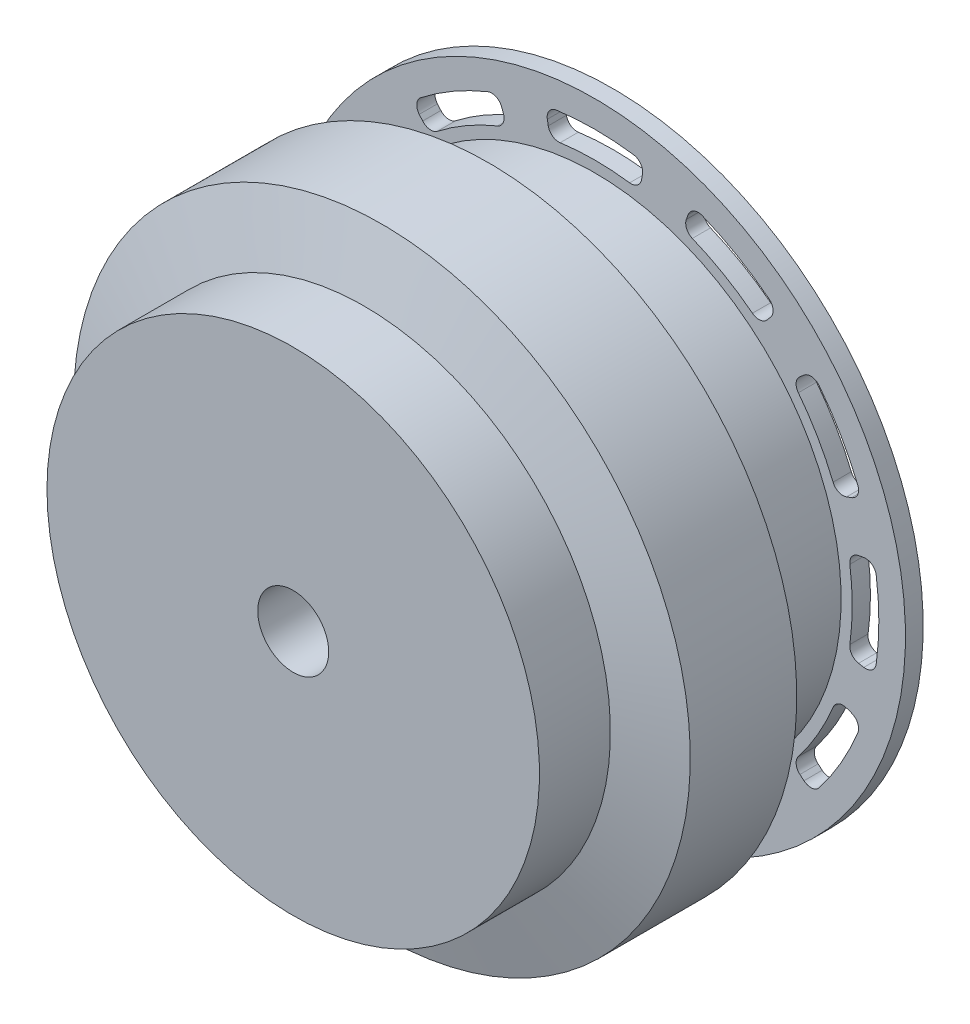
SolidWorks part; units mm, degrees
ref_plane "Plan de face" through (0, 0, 0) normal (0, 0, 1) x (1, 0, 0)
ref_plane "Plan de dessus" through (0, 0, 0) normal (0, 1, 0) x (1, 0, 0)
ref_plane "Plan de droite" through (0, 0, 0) normal (1, 0, 0) x (0, 0, -1)
sketch "Esquisse2" plane through (0, 0, 0) normal (0, 1, 0) x (1, 0, 0)
  line L0 (-13.875, -5) -> (-17.375, -5) construction
  line L1 (-17.375, -5) -> (-17.375, -13) construction
  line L2 (-13.875, 0) -> (-13.875, -3.6273) construction
  line L3 (-13.875, -3.6273) -> (15.125, -3.6273) construction
  line L4 (15.125, -3.6273) -> (15.125, 0) construction
  line L5 (0, 11.4518) -> (0, -9.7046) construction
  line L6 (-17.5, 1) -> (-17.5, 0) construction
  line L7 (-17.375, -13) -> (-13.875, -13) construction
  line L8 (-8.9586, -1.6125) -> (8.1668, -1.6125) construction
  line L9 (-17.5, 1) -> (-17.5, 0)
  line L10 (-17.5, 0) -> (-13.875, 0)
  line L11 (-13.875, 0) -> (-13.875, -5)
  line L12 (0, -1.6125) -> (0, -17)
  line L13 (0, -17) -> (-13.875, -17)
  line L14 (-17.375, -9) -> (-13.875, -9) construction
  line L15 (-17.375, -6) -> (-13.875, -5)
  line L16 (-17.375, -12) -> (-13.875, -13)
  line L17 (-17.375, -6) -> (-17.375, -12)
  line L18 (-13.875, -13) -> (-13.875, -17)
  spline S0 degree 3 poles (-17.5, 1) (1.0335, 1.3329) (-9.7673, -1.5554) (0, -1.6125) knots 0 0 0 0 1 1 1 1
  spline S1 degree 3 poles (17.5, 1) (-1.0335, 1.3329) (9.7673, -1.5554) (0, -1.6125) knots 0 0 0 0 1 1 1 1
  point P5 (0, 0)
  dimension "D1" = 29
  dimension "D2" = 1
  dimension "D3" = 13.875
  dimension "D4" = 17
  dimension "D5" = 5
  dimension "D6" = 8
  dimension "D7" = 3.5
  dimension "D8" = 6
revolve "Révolution1" add sketch "Esquisse2" angle 360 about L5
sketch "Esquisse3" plane through (0, 0, 0) normal (0, 0, 1) x (1, 0, 0)
  circle A0 centre (0, 0) radius 3
  circle A1 centre (0, 0) radius 2 construction
  dimension "D1" = 4
  dimension "D2" = 6
extrude "Boss.-Extru.1" add sketch "Esquisse3" along normal blind 3.4 separate body
fillet "Congé1" radius 1 1 edges at (3, 0, 0)
sketch "Esquisse4" plane through (0, 0, 0) normal (0, 0, 1) x (1, 0, 0)
  line L0 (0, 16.53) -> (0, 13.5518) construction
  line L1 (-2.6806, 15.153) -> (-2.6283, 14.8574)
  line L2 (2.6806, 15.153) -> (2.6283, 14.8574)
  line L3 (5.255, 14.4632) -> (5.1525, 14.181)
  line L4 (9.898, 11.7826) -> (9.7049, 11.5527)
  line L5 (11.7826, 9.898) -> (11.5527, 9.7049)
  line L6 (14.4632, 5.255) -> (14.181, 5.1525)
  line L7 (15.153, 2.6806) -> (14.8574, 2.6283)
  line L8 (15.153, -2.6806) -> (14.8574, -2.6283)
  line L9 (14.4632, -5.255) -> (14.181, -5.1525)
  line L10 (11.7826, -9.898) -> (11.5527, -9.7049)
  line L11 (9.898, -11.7826) -> (9.7049, -11.5527)
  line L12 (5.255, -14.4632) -> (5.1525, -14.181)
  line L13 (2.6806, -15.153) -> (2.6283, -14.8574)
  line L14 (-2.6806, -15.153) -> (-2.6283, -14.8574)
  line L15 (-5.255, -14.4632) -> (-5.1525, -14.181)
  line L16 (-9.898, -11.7826) -> (-9.7049, -11.5527)
  line L17 (-11.7826, -9.898) -> (-11.5527, -9.7049)
  line L18 (-14.4632, -5.255) -> (-14.181, -5.1525)
  line L19 (-15.153, -2.6806) -> (-14.8574, -2.6283)
  line L20 (-15.153, 2.6806) -> (-14.8574, 2.6283)
  line L21 (-14.4632, 5.255) -> (-14.181, 5.1525)
  line L22 (-11.7826, 9.898) -> (-11.5527, 9.7049)
  line L23 (-9.898, 11.7826) -> (-9.7049, 11.5527)
  line L24 (-5.255, 14.4632) -> (-5.1525, 14.181)
  arc A0 (2.1712, 15.852) -> (-2.1712, 15.852) centre (0, 0) ccw
  arc A3 (1.9565, 14.3674) -> (-1.9565, 14.3674) centre (0, 0) ccw
  arc A4 (2.6283, 14.8574) -> (1.9565, 14.3674) centre (2.0375, 14.9619) cw
  arc A5 (2.6806, 15.153) -> (2.1712, 15.852) centre (2.0898, 15.2575) ccw
  arc A6 (-2.6806, 15.153) -> (-2.1712, 15.852) centre (-2.0898, 15.2575) cw
  arc A7 (-2.6283, 14.8574) -> (-1.9565, 14.3674) centre (-2.0375, 14.9619) ccw
  arc A8 (9.8063, 12.6426) -> (6.0457, 14.8138) centre (0, 0) ccw
  arc A9 (5.255, 14.4632) -> (6.0457, 14.8138) centre (5.819, 14.2583) cw
  arc A10 (9.898, 11.7826) -> (9.8063, 12.6426) centre (9.4386, 12.1685) ccw
  arc A11 (5.1525, 14.181) -> (5.4893, 13.4208) centre (5.7164, 13.9761) ccw
  arc A12 (8.8781, 11.4643) -> (5.4893, 13.4208) centre (0, 0) ccw
  arc A13 (9.7049, 11.5527) -> (8.8781, 11.4643) centre (9.2455, 11.9387) cw
  arc A14 (14.8138, 6.0457) -> (12.6426, 9.8063) centre (0, 0) ccw
  arc A15 (11.7826, 9.898) -> (12.6426, 9.8063) centre (12.1685, 9.4386) cw
  arc A16 (14.4632, 5.255) -> (14.8138, 6.0457) centre (14.2583, 5.819) ccw
  arc A17 (11.5527, 9.7049) -> (11.4643, 8.8781) centre (11.9387, 9.2455) ccw
  arc A18 (13.4208, 5.4893) -> (11.4643, 8.8781) centre (0, 0) ccw
  arc A19 (14.181, 5.1525) -> (13.4208, 5.4893) centre (13.9761, 5.7164) cw
  arc A20 (15.852, -2.1712) -> (15.852, 2.1712) centre (0, 0) ccw
  arc A21 (15.153, 2.6806) -> (15.852, 2.1712) centre (15.2575, 2.0898) cw
  arc A22 (15.153, -2.6806) -> (15.852, -2.1712) centre (15.2575, -2.0898) ccw
  arc A23 (14.8574, 2.6283) -> (14.3674, 1.9565) centre (14.9619, 2.0375) ccw
  arc A24 (14.3674, -1.9565) -> (14.3674, 1.9565) centre (0, 0) ccw
  arc A25 (14.8574, -2.6283) -> (14.3674, -1.9565) centre (14.9619, -2.0375) cw
  arc A26 (12.6426, -9.8063) -> (14.8138, -6.0457) centre (0, 0) ccw
  arc A27 (14.4632, -5.255) -> (14.8138, -6.0457) centre (14.2583, -5.819) cw
  arc A28 (11.7826, -9.898) -> (12.6426, -9.8063) centre (12.1685, -9.4386) ccw
  arc A29 (14.181, -5.1525) -> (13.4208, -5.4893) centre (13.9761, -5.7164) ccw
  arc A30 (11.4643, -8.8781) -> (13.4208, -5.4893) centre (0, 0) ccw
  arc A31 (11.5527, -9.7049) -> (11.4643, -8.8781) centre (11.9387, -9.2455) cw
  arc A32 (6.0457, -14.8138) -> (9.8063, -12.6426) centre (0, 0) ccw
  arc A33 (9.898, -11.7826) -> (9.8063, -12.6426) centre (9.4386, -12.1685) cw
  arc A34 (5.255, -14.4632) -> (6.0457, -14.8138) centre (5.819, -14.2583) ccw
  arc A35 (9.7049, -11.5527) -> (8.8781, -11.4643) centre (9.2455, -11.9387) ccw
  arc A36 (5.4893, -13.4208) -> (8.8781, -11.4643) centre (0, 0) ccw
  arc A37 (5.1525, -14.181) -> (5.4893, -13.4208) centre (5.7164, -13.9761) cw
  arc A38 (-2.1712, -15.852) -> (2.1712, -15.852) centre (0, 0) ccw
  arc A39 (2.6806, -15.153) -> (2.1712, -15.852) centre (2.0898, -15.2575) cw
  arc A40 (-2.6806, -15.153) -> (-2.1712, -15.852) centre (-2.0898, -15.2575) ccw
  arc A41 (2.6283, -14.8574) -> (1.9565, -14.3674) centre (2.0375, -14.9619) ccw
  arc A42 (-1.9565, -14.3674) -> (1.9565, -14.3674) centre (0, 0) ccw
  arc A43 (-2.6283, -14.8574) -> (-1.9565, -14.3674) centre (-2.0375, -14.9619) cw
  arc A44 (-9.8063, -12.6426) -> (-6.0457, -14.8138) centre (0, 0) ccw
  arc A45 (-5.255, -14.4632) -> (-6.0457, -14.8138) centre (-5.819, -14.2583) cw
  arc A46 (-9.898, -11.7826) -> (-9.8063, -12.6426) centre (-9.4386, -12.1685) ccw
  arc A47 (-5.1525, -14.181) -> (-5.4893, -13.4208) centre (-5.7164, -13.9761) ccw
  arc A48 (-8.8781, -11.4643) -> (-5.4893, -13.4208) centre (0, 0) ccw
  arc A49 (-9.7049, -11.5527) -> (-8.8781, -11.4643) centre (-9.2455, -11.9387) cw
  arc A50 (-14.8138, -6.0457) -> (-12.6426, -9.8063) centre (0, 0) ccw
  arc A51 (-11.7826, -9.898) -> (-12.6426, -9.8063) centre (-12.1685, -9.4386) cw
  arc A52 (-14.4632, -5.255) -> (-14.8138, -6.0457) centre (-14.2583, -5.819) ccw
  arc A53 (-11.5527, -9.7049) -> (-11.4643, -8.8781) centre (-11.9387, -9.2455) ccw
  arc A54 (-13.4208, -5.4893) -> (-11.4643, -8.8781) centre (0, 0) ccw
  arc A55 (-14.181, -5.1525) -> (-13.4208, -5.4893) centre (-13.9761, -5.7164) cw
  arc A56 (-15.852, 2.1712) -> (-15.852, -2.1712) centre (0, 0) ccw
  arc A57 (-15.153, -2.6806) -> (-15.852, -2.1712) centre (-15.2575, -2.0898) cw
  arc A58 (-15.153, 2.6806) -> (-15.852, 2.1712) centre (-15.2575, 2.0898) ccw
  arc A59 (-14.8574, -2.6283) -> (-14.3674, -1.9565) centre (-14.9619, -2.0375) ccw
  arc A60 (-14.3674, 1.9565) -> (-14.3674, -1.9565) centre (0, 0) ccw
  arc A61 (-14.8574, 2.6283) -> (-14.3674, 1.9565) centre (-14.9619, 2.0375) cw
  arc A62 (-12.6426, 9.8063) -> (-14.8138, 6.0457) centre (0, 0) ccw
  arc A63 (-14.4632, 5.255) -> (-14.8138, 6.0457) centre (-14.2583, 5.819) cw
  arc A64 (-11.7826, 9.898) -> (-12.6426, 9.8063) centre (-12.1685, 9.4386) ccw
  arc A65 (-14.181, 5.1525) -> (-13.4208, 5.4893) centre (-13.9761, 5.7164) ccw
  arc A66 (-11.4643, 8.8781) -> (-13.4208, 5.4893) centre (0, 0) ccw
  arc A67 (-11.5527, 9.7049) -> (-11.4643, 8.8781) centre (-11.9387, 9.2455) cw
  arc A68 (-6.0457, 14.8138) -> (-9.8063, 12.6426) centre (0, 0) ccw
  arc A69 (-9.898, 11.7826) -> (-9.8063, 12.6426) centre (-9.4386, 12.1685) cw
  arc A70 (-5.255, 14.4632) -> (-6.0457, 14.8138) centre (-5.819, 14.2583) ccw
  arc A71 (-9.7049, 11.5527) -> (-8.8781, 11.4643) centre (-9.2455, 11.9387) ccw
  arc A72 (-5.4893, 13.4208) -> (-8.8781, 11.4643) centre (0, 0) ccw
  arc A73 (-5.1525, 14.181) -> (-5.4893, 13.4208) centre (-5.7164, 13.9761) cw
  point P10 (2.5259, 14.2783)
  point P13 (2.7872, 15.7554)
  point P16 (-2.7872, 15.7554)
  point P19 (-2.5259, 14.2783)
  point P154 (0, 0)
  dimension "D1" = 1.5
  dimension "D2" = 0.6
  dimension "D3" = 12
extrude "Enlèv. mat.-Extru.1" cut sketch "Esquisse4" against normal mid plane 10
sketch "Esquisse5" plane through (0, 0, 17) normal (0, 0, 1) x (1, 0, 0)
  circle A0 centre (0, 0) radius 2
  dimension "D1" = 4
extrude "Enlèv. mat.-Extru.2" cut sketch "Esquisse5" against normal blind 15
